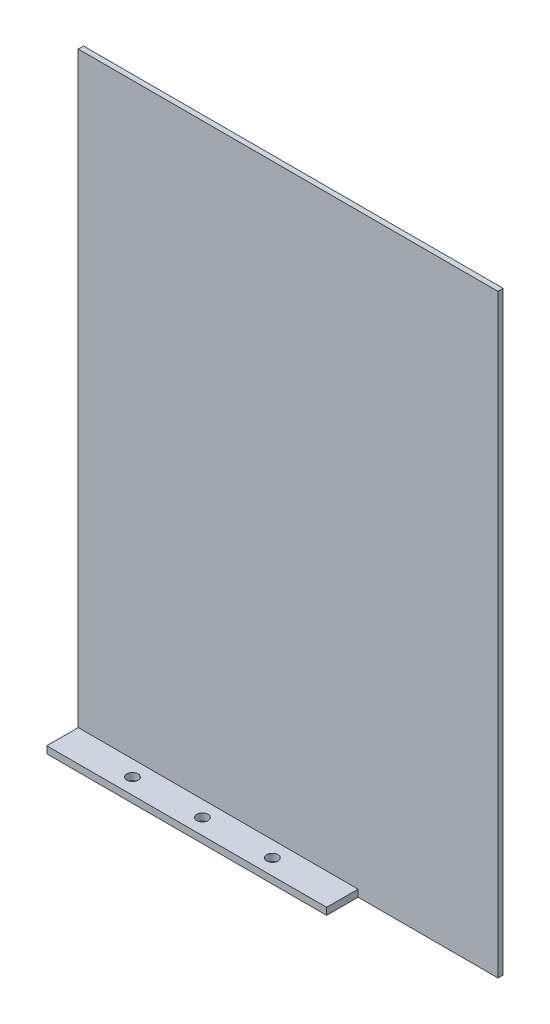
SolidWorks part; units mm, degrees
ref_plane "前视基准面" through (0, 0, 0) normal (0, 0, 1) x (1, 0, 0)
ref_plane "上视基准面" through (0, 0, 0) normal (0, 1, 0) x (1, 0, 0)
ref_plane "右视基准面" through (0, 0, 0) normal (1, 0, 0) x (0, 0, -1)
sketch "草图1" plane through (0, 0, 0) normal (0, 0, 1) x (1, 0, 0)
  line L1 (0, 0) -> (120, 0)
  line L2 (0, 0) -> (0, -170)
  line L3 (0, -170) -> (120, -170)
  line L4 (120, 0) -> (120, -170)
extrude "凸台-拉伸1" add sketch "草图1" along normal blind 1.5
sketch "草图2" plane through (0, 0, 1.5) normal (0, 0, 1) x (1, 0, 0)
  line L1 (0, -170) -> (80, -170)
  line L2 (0, -170) -> (0, -168)
  line L3 (0, -168) -> (80, -168)
  line L4 (80, -170) -> (80, -168)
extrude "凸台-拉伸2" add sketch "草图2" along normal blind 9
sketch "草图3" plane through (0, -168, 0) normal (0, 1, 0) x (1, 0, 0)
  line L0 (80, -10.5) -> (0, -10.5) construction
  circle A0 centre (20, -6) radius 1.6
  circle A1 centre (40, -6) radius 1.6
  circle A2 centre (60, -6) radius 1.6
  point P0 (20, -10.5)
  point P1 (40, -10.5)
  point P4 (60, -10.5)
  point P5 (0, -10.5)
  point P8 (20, -6)
  point P10 (40, -6)
  point P11 (60, -6)
  dimension "D1" = 20
  dimension "D2" = 20
extrude "切除-拉伸1" cut sketch "草图3" against normal blind 9
